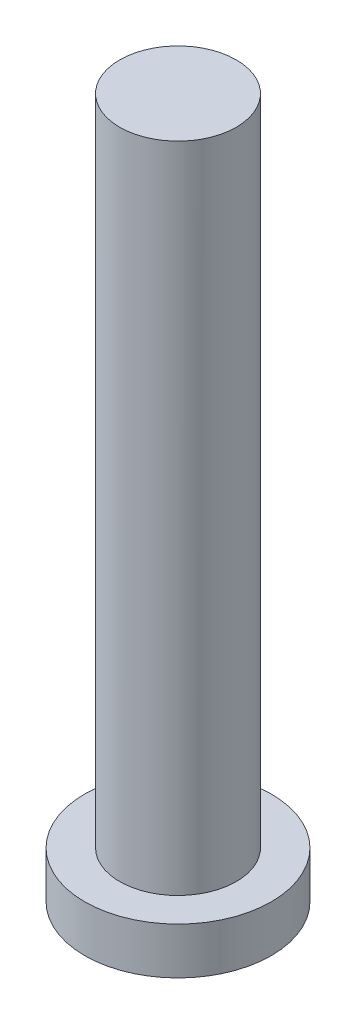
SolidWorks part; units mm, degrees
ref_plane "Front Plane" through (0, 0, 0) normal (0, 0, 1) x (1, 0, 0)
ref_plane "Top Plane" through (0, 0, 0) normal (0, 1, 0) x (1, 0, 0)
ref_plane "Right Plane" through (0, 0, 0) normal (1, 0, 0) x (0, 0, -1)
sketch "Sketch2" plane through (0, 0, 0) normal (0, 1, 0) x (1, 0, 0)
  circle A0 centre (0, 0) radius 1.25
extrude "Boss-Extrude1" add sketch "Sketch2" along normal blind 14
sketch "Sketch3" plane through (0, 0, 0) normal (0, -1, 0) x (1, 0, 0)
  circle A0 centre (0, 0) radius 2
extrude "Boss-Extrude2" add sketch "Sketch3" along normal blind 1
